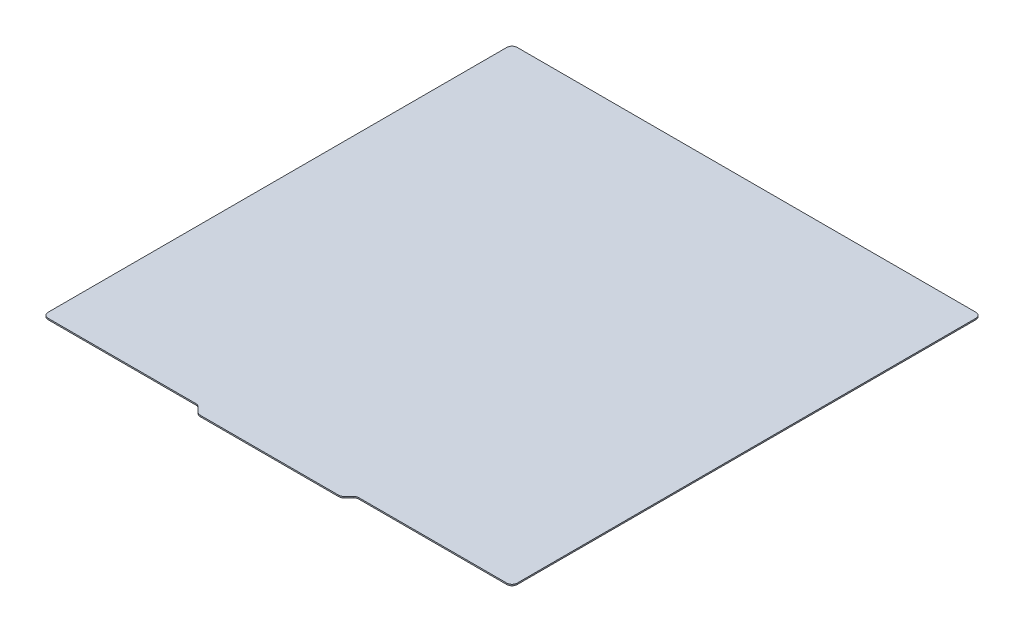
SolidWorks part; units mm, degrees
material "Alloy Steel"
ref_plane "Front Plane" through (0, 0, 0) normal (0, 0, 1) x (1, 0, 0)
ref_plane "Top Plane" through (0, 0, 0) normal (0, 1, 0) x (1, 0, 0)
ref_plane "Right Plane" through (0, 0, 0) normal (1, 0, 0) x (0, 0, -1)
sketch "Sketch1" plane through (0, 0, 0) normal (0, 1, 0) x (1, 0, 0)
  line L0 (-60, -177.5) -> (-54, -183.5)
  line L1 (-177.5, 177.5) -> (177.5, 177.5)
  line L2 (-177.5, 177.5) -> (-177.5, -177.5)
  line L3 (-177.5, -177.5) -> (-60, -177.5)
  line L4 (177.5, 177.5) -> (177.5, -177.5)
  line L5 (-177.5, 177.5) -> (177.5, -177.5) construction
  line L6 (-177.5, -177.5) -> (177.5, 177.5) construction
  line L7 (-54, -183.5) -> (54, -183.5)
  line L8 (54, -183.5) -> (60, -177.5)
  line L9 (-60, -177.5) -> (60, -177.5) construction
  line L10 (60, -177.5) -> (177.5, -177.5)
  point P0 (0, 0)
  point P8 (0, -183.5)
  point P11 (0, -177.5)
  dimension "D1" = 355
  dimension "D2" = 45
  dimension "D3" = 120
  dimension "D4" = 6
extrude "Boss-Extrude1" add sketch "Sketch1" along normal blind 1
fillet "Fillet1" radius 4 8 edges at (177.5, 0.5, -177.5) (-177.5, 0.5, -177.5) (-177.5, 0.5, 177.5) (-54, 0.5, 183.5) (-60, 0.5, 177.5) (54, 0.5, 183.5) (60, 0.5, 177.5) (177.5, 0.5, 177.5)
